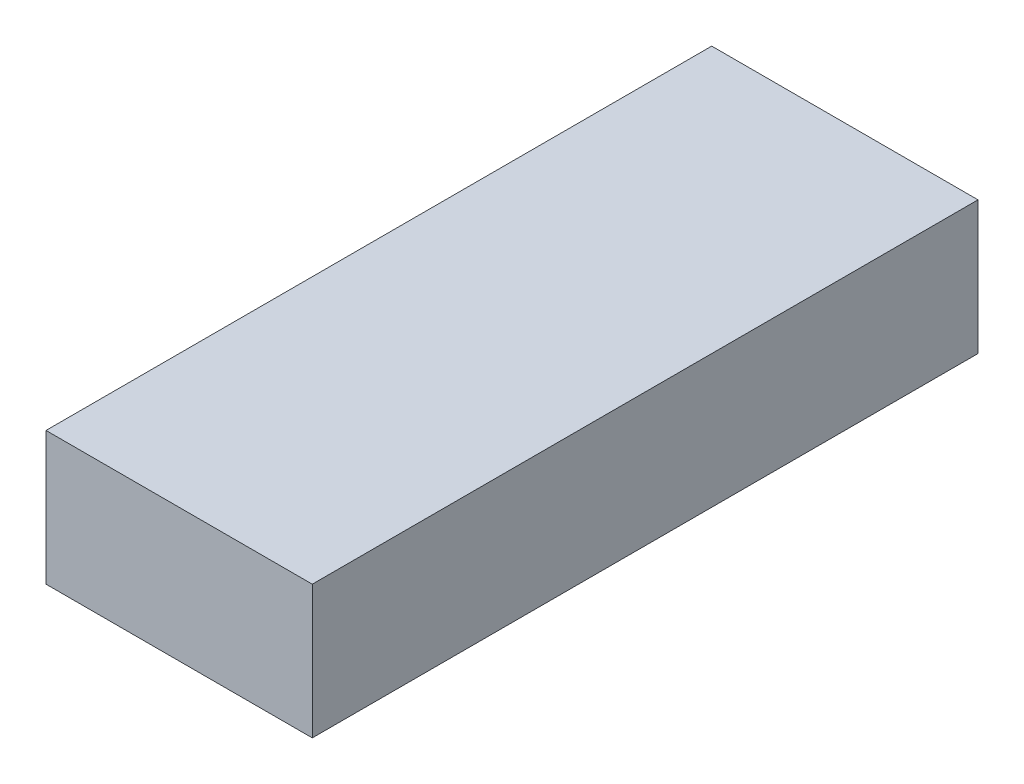
SolidWorks part; units mm, degrees
ref_plane "前视基准面" through (0, 0, 0) normal (0, 0, 1) x (1, 0, 0)
ref_plane "上视基准面" through (0, 0, 0) normal (0, 1, 0) x (1, 0, 0)
ref_plane "右视基准面" through (0, 0, 0) normal (1, 0, 0) x (0, 0, -1)
sketch "草图1" plane through (0, 0, 0) normal (0, 1, 0) x (1, 0, 0)
  line L1 (0, 0) -> (20, 0)
  line L2 (0, 0) -> (0, 50)
  line L3 (0, 50) -> (20, 50)
  line L4 (20, 0) -> (20, 50)
  dimension "D1" = 50
  dimension "D2" = 20
extrude "凸台-拉伸1" add sketch "草图1" along normal blind 10
